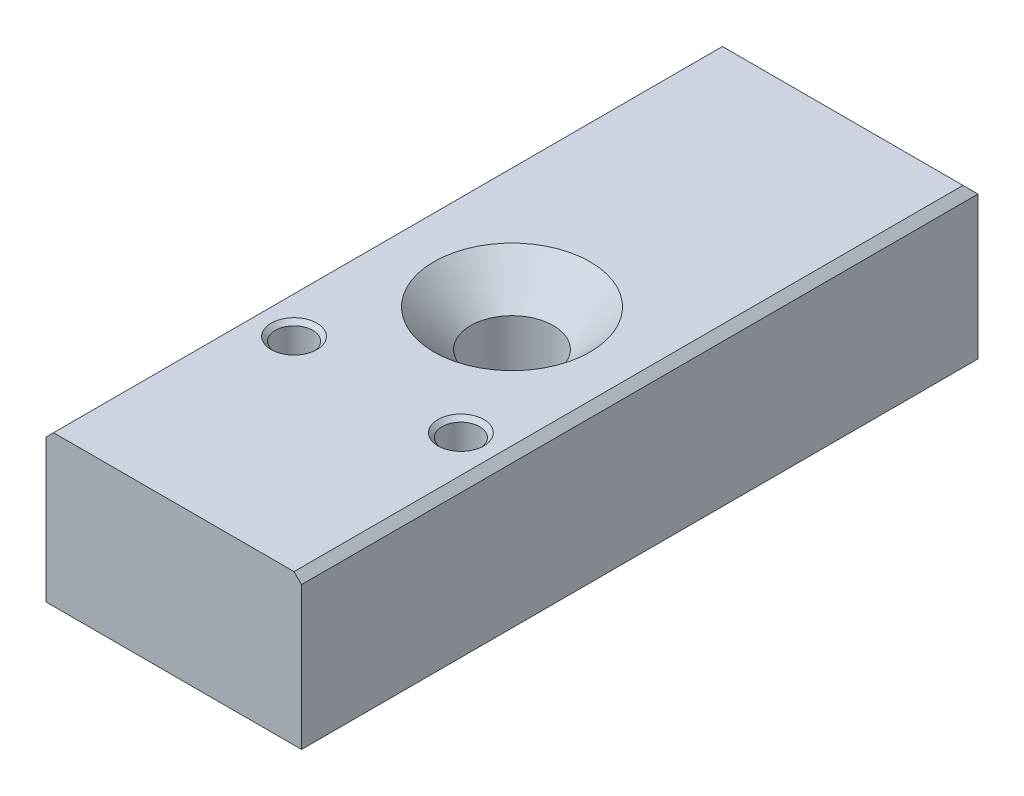
SolidWorks part; units mm, degrees
material "3.1355 (EN-AW 2024)"
ref_plane "Front" through (0, 0, 0) normal (0, 0, 1) x (1, 0, 0)
ref_plane "Top" through (0, 0, 0) normal (0, 1, 0) x (1, 0, 0)
ref_plane "Right" through (0, 0, 0) normal (1, 0, 0) x (0, 0, -1)
sketch "Эскиз1" plane through (0, 0, 0) normal (0, 1, 0) x (1, 0, 0)
  line L1 (-8.5, 22.5) -> (8.5, 22.5)
  line L2 (-8.5, 22.5) -> (-8.5, -22.5)
  line L3 (-8.5, -22.5) -> (8.5, -22.5)
  line L4 (8.5, 22.5) -> (8.5, -22.5)
  line L5 (-8.5, 22.5) -> (8.5, -22.5) construction
  line L6 (-8.5, -22.5) -> (8.5, 22.5) construction
  point P0 (0, 0)
  dimension "D1" = 45
  dimension "D2" = 17
extrude "База" add sketch "Эскиз1" along normal blind 10
hole_wizard "Крепление к профилю 40 - M5" positions "Эскиз2" profile "Эскиз3" countersink size "M5" standard "DIN" end condition through all
sketch "Эскиз2" plane through (0, 10, 0) normal (0, 1, 0) x (-1, 0, 0)
  point P0 (0, 0)
sketch "Эскиз3" plane through (0, 10, 0) normal (1, 0, 0) x (0, 0, 1)
  line L0 (0, 0) -> (0, 10)
  line L1 (0, 10) -> (2.75, 10)
  line L2 (2.75, 10) -> (2.75, 2.45)
  line L3 (2.75, 2.45) -> (5.2, 0)
  line L5 (5.2, 0) -> (0, 0)
  line L6 (-2.75, 2.45) -> (-5.2, 0) construction
  line L11 (0, -6.35) -> (0, 107.95) construction
  dimension "Диаметр сквозного отверстия" = 5.5
  dimension "Глубина сквозного отверстия" = 10
  dimension "Диаметр передней зенковки" = 10.4
  dimension "Угол передней зенковки" = 90
hole_wizard "Крепление датчика" positions "Эскиз6" profile "Эскиз5" tap size "M3" standard "DIN" end condition through all
sketch "Эскиз6" plane through (0, 10, 0) normal (0, 1, 0) x (-1, 0, 0)
  line L0 (5.55, 8.95) -> (0, 8.95) construction
  line L1 (0, 8.95) -> (-5.55, 8.95) construction
  point P0 (5.55, 8.95)
  point P3 (-5.55, 8.95)
  dimension "D1" = 11.1
  dimension "D2" = 8.95
sketch "Эскиз5" plane through (-5.55, 10, 8.95) normal (1, 0, 0) x (0, 0, 1)
  line L0 (0, 0) -> (0, 10)
  line L1 (0, 10) -> (1.25, 10)
  line L2 (1.25, 10) -> (1.25, 0.275)
  line L3 (1.25, 0.275) -> (1.525, 0)
  line L5 (1.525, 0) -> (0, 0)
  line L6 (-1.25, 0.275) -> (-1.525, 0) construction
  line L11 (0, -6.35) -> (0, 107.95) construction
  dimension "Диаметр проходного сверла" = 2.5
  dimension "Глубина проходного сверла" = 10
  dimension "Диаметр передней зенковки" = 3.05
  dimension "Угол передней зенковки" = 90
cosmetic thread "Отверстие резьбы1"
cosmetic thread "Отверстие резьбы2"
chamfer "Фаска1" distance 0.5 angle 45 4 edges at (0, 10, 22.5) (8.5, 10, 0) (0, 10, -22.5) (-8.5, 10, 0)
